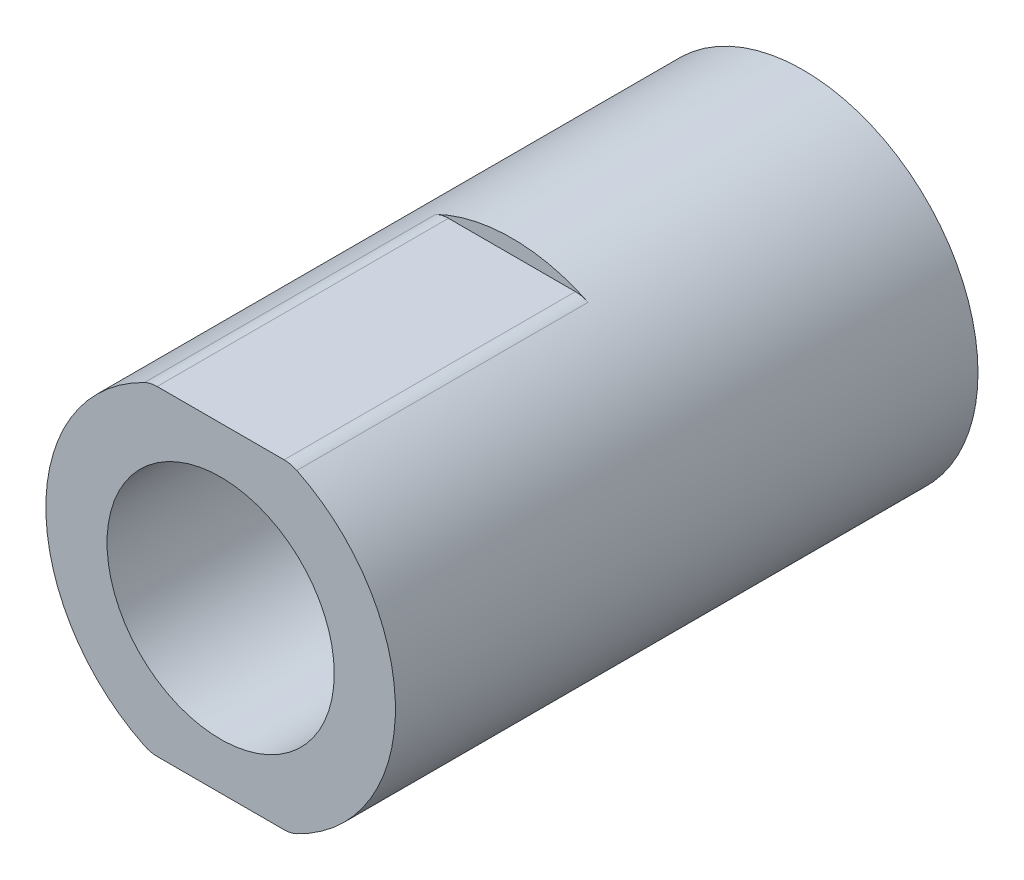
SolidWorks part; units mm, degrees
ref_plane "Front Plane" through (0, 0, 0) normal (0, 0, 1) x (1, 0, 0)
ref_plane "Top Plane" through (0, 0, 0) normal (0, 1, 0) x (1, 0, 0)
ref_plane "Right Plane" through (0, 0, 0) normal (1, 0, 0) x (0, 0, -1)
sketch "Sketch1" plane through (0, 0, 0) normal (0, 0, 1) x (1, 0, 0)
  circle A0 centre (0, 0) radius 6
  circle A1 centre (0, 0) radius 2.4
  circle A3 centre (0, 0) radius 1.5 construction
  dimension "D1" = 4.8
  dimension "D2" = 12
  dimension "D5" = 3
extrude "Boss-Extrude1" add sketch "Sketch1" along normal blind 20
sketch "Sketch2" plane through (0, 0, 20) normal (0, 0, 1) x (1, 0, 0)
  circle A0 centre (0, 0) radius 3.9
  point P2 (0, 0)
  dimension "D1" = 7.8
extrude "Cut-Extrude1" cut sketch "Sketch2" against normal blind 7.5
sketch "Sketch4" plane through (0, 0, 20) normal (0, 0, 1) x (1, 0, 0)
  line L0 (-2.3979, 5.5) -> (2.3979, 5.5)
  line L2 (2.3979, -5.5) -> (-2.3979, -5.5)
  arc A0 (2.3979, 5.5) -> (-2.3979, 5.5) centre (0, 0) ccw
  arc A1 (2.3979, -5.5) -> (-2.3979, -5.5) centre (0, 0) cw
  circle A3 centre (0, 0) radius 6 construction
  dimension "D1" = 11
extrude "Cut-Extrude2" cut sketch "Sketch4" against normal blind 10
fillet "Fillet1" radius 1 4 edges at (2.3979, -5.5, 15) (-2.3979, -5.5, 15) (-2.3979, 5.5, 15) (2.3979, 5.5, 15)
